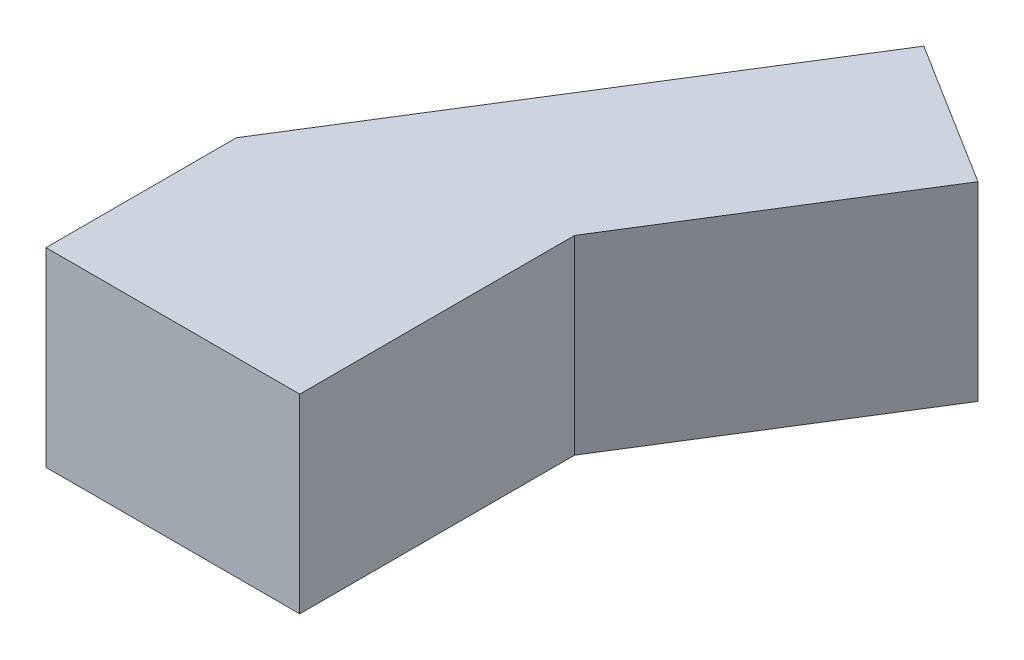
SolidWorks part; units mm, degrees
ref_plane "前视基准面" through (0, 0, 0) normal (0, 0, 1) x (1, 0, 0)
ref_plane "上视基准面" through (0, 0, 0) normal (0, 1, 0) x (1, 0, 0)
ref_plane "右视基准面" through (0, 0, 0) normal (1, 0, 0) x (0, 0, -1)
sketch "草图1" plane through (0, 0, 0) normal (0, 1, 0) x (1, 0, 0)
  line L0 (0, 0) -> (24, 0)
  line L1 (24, 0) -> (24, 26)
  line L2 (0, 0) -> (0, 18)
  line L3 (24, 26) -> (38.6728, 49.4814)
  line L4 (0, 18) -> (25.0075, 58.0204)
  line L5 (25.0075, 58.0204) -> (38.6728, 49.4814)
  point P7 (0, 14)
  point P8 (24, 28)
  dimension "D1" = 24
  dimension "D2" = 26
  dimension "D3" = 18
  dimension "D4" = 148
extrude "凸台-拉伸1" add sketch "草图1" along normal blind 18
ref_point "点1"
equation "\"zz_zj\"= 16'中指直径"
equation "\"zz_1cd\"= 24'中指根1节长度"
equation "\"zz_2cd\"= 23'中指根2节长度"
equation "\"zz_3cd\"= 21'中指根3节长度"
equation "\"wz_zj\"= 16'无名指直径"
equation "\"wz_1cd\"= 24'无名指根1节长度"
equation "\"wz_2cd\"= 23'无名指根2节长度"
equation "\"wz_3cd\"= 21'无名指根3节长度"
equation "\"xz_zj\"= 16'小指直径"
equation "\"xz_1cd\"= 22'小指根1节长度"
equation "\"xz_2cd\"= 18'小指根2节长度"
equation "\"xz_3cd\"= 18'小指根3节长度"
equation "\"D1@凸台-拉伸1\"=\"zz_zj\"+2"
